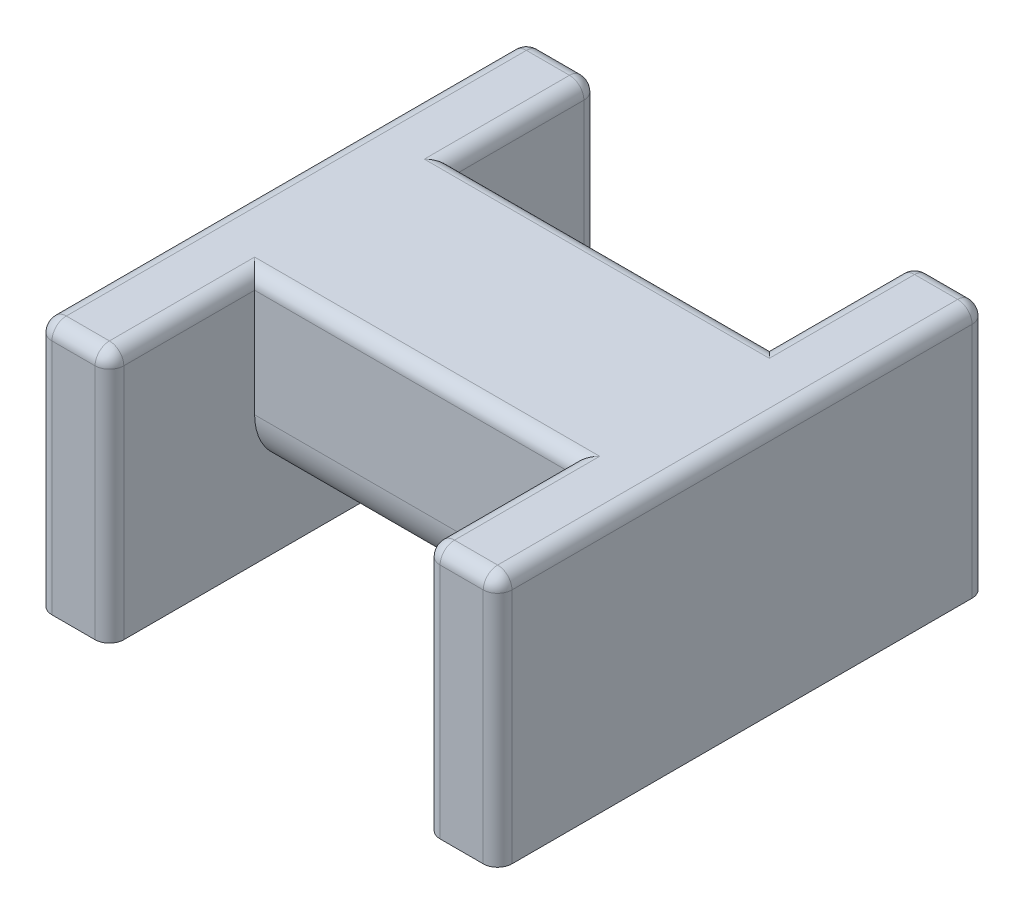
SolidWorks part; units mm, degrees
ref_plane "Front Plane" through (0, 0, 0) normal (0, 0, 1) x (1, 0, 0)
ref_plane "Top Plane" through (0, 0, 0) normal (0, 1, 0) x (1, 0, 0)
ref_plane "Right Plane" through (0, 0, 0) normal (1, 0, 0) x (0, 0, -1)
sketch "Sketch1" plane through (0, 0, 0) normal (1, 0, 0) x (0, 0, -1)
  line L0 (-17, 7.25) -> (17, 7.25)
  line L1 (-6.9, -5.25) -> (6.9, -5.25)
  line L2 (-6.9, -5.25) -> (-6.9, 5.25)
  line L3 (-6.9, 5.25) -> (6.9, 5.25)
  line L4 (6.9, -5.25) -> (6.9, 5.25)
  line L5 (-6.9, -5.25) -> (6.9, 5.25) construction
  line L6 (-6.9, 5.25) -> (6.9, -5.25) construction
  line L7 (-17, 7.25) -> (-17, 5.25)
  line L8 (-17, 5.25) -> (-6.9, 5.25)
  line L9 (6.9, 5.25) -> (17, 5.25)
  line L10 (17, 5.25) -> (17, 7.25)
  point P0 (0, 0)
  point P9 (0, 7.25)
  dimension "D1" = 13.8
  dimension "D2" = 10.5
  dimension "D3" = 34
  dimension "D4" = 2
extrude "Boss-Extrude1" add sketch "Sketch1" along normal blind 22 contours L9 L10 L0 L7 L8 L3 | L1 L4 L3 L2
sketch "Sketch2" plane through (22, 0, 0) normal (1, 0, 0) x (0, 0, -1)
  line L0 (-17, 7.25) -> (17, 7.25) construction
  line L1 (-17, 7.25) -> (17, 7.25)
  line L3 (-17, 7.25) -> (17, 7.25)
  line L4 (-17, 7.25) -> (-17, -10.25)
  line L5 (-17, -10.25) -> (17, -10.25)
  line L6 (17, 7.25) -> (17, -10.25)
  line M5 (-17, 5.25) -> (-6.9, 5.25)
  line M6 (-6.9, 5.25) -> (-6.9, -5.25)
  line M7 (-6.9, -5.25) -> (6.9, -5.25)
  line M8 (6.9, -5.25) -> (6.9, 5.25)
  line M9 (6.9, 5.25) -> (17, 5.25)
  line M10 (17, 5.25) -> (17, 7.25)
  line M11 (17, 7.25) -> (-17, 7.25)
  line M12 (-17, 7.25) -> (-17, 5.25)
  dimension "D1" = 17.5
extrude "Boss-Extrude2" add sketch "Sketch2" along normal blind 5 contours L6 L4 L5 M9 M8 M7 M6 M5 | M12 M5 M6 M7 M8 M9 M10 M11
sketch "Sketch3" plane through (0, 0, 0) normal (-1, 0, 0) x (0, 0, 1)
  line L0 (17, 7.25) -> (-17, 7.25) construction
  line L1 (17, 7.25) -> (-17, 7.25) construction
  line L2 (17, 7.25) -> (17, -10.25) construction
  line L3 (17, -10.25) -> (-17, -10.25) construction
  line L4 (-17, 7.25) -> (-17, -10.25) construction
  line L5 (17, 7.25) -> (-17, 7.25)
  line L6 (17, 7.25) -> (-17, 7.25)
  line L7 (17, 7.25) -> (17, -10.25)
  line L8 (17, -10.25) -> (-17, -10.25)
  line L9 (-17, 7.25) -> (-17, -10.25)
  line M1 (6.9, 5.25) -> (17, 5.25)
  line M2 (17, 5.25) -> (17, 7.25)
  line M3 (17, 7.25) -> (-17, 7.25)
  line M4 (-17, 7.25) -> (-17, 5.25)
  line M5 (-17, 5.25) -> (-6.9, 5.25)
  line M6 (-6.9, 5.25) -> (-6.9, -5.25)
  line M7 (-6.9, -5.25) -> (6.9, -5.25)
  line M8 (6.9, -5.25) -> (6.9, 5.25)
extrude "Boss-Extrude3" add sketch "Sketch3" along normal blind 5 contours L9 L8 L7 M5 M1 M8 M7 M6 | M8 M1 M2 M3 M4 M5 M6 M7
sketch "Sketch4" plane through (0, -10.25, 0) normal (0, -1, 0) x (1, 0, 0)
  line L0 (0, 0) -> (-5, 0) construction
  line L2 (11, 17) -> (11, -17) construction
  line L3 (22, 17) -> (0, 17) construction
  line L4 (0, -17) -> (0, 17)
  line L5 (0, 17) -> (-5, 17)
  line L6 (-5, 17) -> (-5, -17)
  line L7 (-5, -17) -> (0, -17)
  line L8 (0, -17) -> (0, 17)
  line L9 (0, 17) -> (-5, 17)
  line L10 (-5, 17) -> (-5, -17)
  line L11 (-5, -17) -> (0, -17)
  line L12 (22, -17) -> (0, -17) construction
  circle A0 centre (-2.5, 0) radius 1.4
  circle A1 centre (24.5, 0) radius 1.4
  dimension "D2" = 2.8
  dimension "D1" = 0
extrude "Cut-Extrude1" cut sketch "Sketch4" against normal blind 8 contours A0 | A1
fillet "Fillet1" [suppressed] radius 1
sketch "Sketch5" plane through (0, 7.25, 0) normal (0, 1, 0) x (1, 0, 0)
  line L4 (0, -6.9) -> (0, -17)
  line L5 (22, -6.9) -> (0, -6.9)
  line L6 (22, -17) -> (22, -6.9)
  line L7 (0, -17) -> (22, -17)
  line L8 (0, -6.9) -> (0, -17)
  line L9 (22, -6.9) -> (0, -6.9)
  line L10 (22, -17) -> (22, -6.9)
  line L11 (0, -17) -> (22, -17)
  line L12 (0, 17) -> (0, 6.9)
  line L13 (22, 17) -> (0, 17)
  line L14 (22, 6.9) -> (22, 17)
  line L15 (0, 6.9) -> (22, 6.9)
  line L16 (0, 17) -> (0, 6.9)
  line L17 (22, 17) -> (0, 17)
  line L18 (22, 6.9) -> (22, 17)
  line L19 (0, 6.9) -> (22, 6.9)
  dimension "D1" = 0
  dimension "D2" = 0
extrude "Cut-Extrude2" cut sketch "Sketch5" against normal through all
fillet "Fillet2" radius 1 20 edges at (24.5, 7.25, 17) (24.5, 7.25, -17) (22, -1.5, -17) (27, -1.5, -17) (22, -1.5, 17) (27, 7.25, 0) (27, -1.5, 17) (-5, -1.5, 17) (0, -1.5, -17) (-5, 7.25, 0) (-5, -1.5, -17) (0, -1.5, 17) (-2.5, 7.25, 17) (-2.5, 7.25, -17) (22, 7.25, 11.95) (11, 7.25, 6.9) (0, 7.25, 11.95) (11, 7.25, -6.9) (22, 7.25, -11.95) (0, 7.25, -11.95)
fillet "Fillet3" radius 4 2 edges at (11, -5.25, -6.9) (11, -5.25, 6.9)
